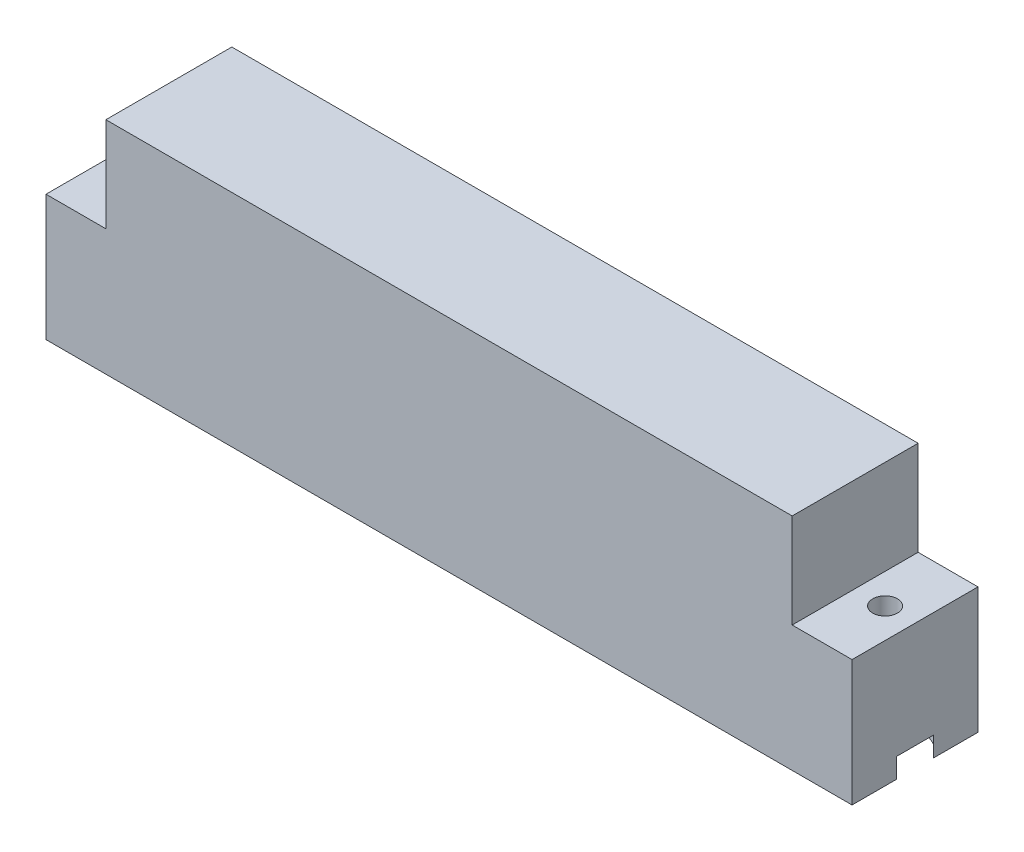
SolidWorks part; units mm, degrees
other "Markup1"
sketch "Sketch8" plane through (81.28, 0, 0) normal (0.1042, -0.9852, 0.1359) x (-0.4456, -0.1684, -0.8792)
ref_plane "Front Plane" through (0, 0, 0) normal (0, 0, 1) x (1, 0, 0)
ref_plane "Top Plane" through (0, 0, 0) normal (0, 1, 0) x (1, 0, 0)
ref_plane "Right Plane" through (0, 0, 0) normal (1, 0, 0) x (0, 0, -1)
sketch "Sketch1" plane through (0, 0, 0) normal (0, 1, 0) x (1, 0, 0)
  line L1 (0, 0) -> (81.28, 0)
  line L2 (0, 0) -> (0, 12.7)
  line L3 (0, 12.7) -> (81.28, 12.7)
  line L4 (81.28, 0) -> (81.28, 12.7)
  line L5 (0, 0) -> (81.28, 12.7) construction
  line L6 (0, 12.7) -> (81.28, 0) construction
  point P4 (40.64, 6.35)
  dimension "D1" = 12.7
  dimension "D2" = 81.28
extrude "Boss-Extrude1" add sketch "Sketch1" along normal blind 12.7
sketch "Sketch2" plane through (0, 12.7, 0) normal (0, 1, 0) x (1, 0, 0)
  line L0 (0, 0) -> (6.0376, 0) construction
  line L1 (0, 0) -> (81.28, 0) construction
  line L2 (81.28, 12.7) -> (0, 12.7) construction
  line L8 (6.0376, 0) -> (75.2424, 0)
  line L9 (6.0376, 0) -> (6.0376, 12.7)
  line L10 (6.0376, 12.7) -> (75.2424, 12.7)
  line L11 (75.2424, 0) -> (75.2424, 12.7)
  line L12 (6.0376, 0) -> (75.2424, 12.7) construction
  line L13 (6.0376, 12.7) -> (75.2424, 0) construction
  line L14 (81.28, 0) -> (81.28, 12.7) construction
  point P7 (14.605, 6.35)
  point P8 (40.64, 6.35)
  point P9 (41.275, 6.35)
  dimension "D1" = 69.2048
  dimension "D2" = 6.0376
  dimension "D3" = 6.0376
extrude "Boss-Extrude2" add sketch "Sketch2" along normal blind 9.525
sketch "Sketch3" plane through (0, 12.7, 0) normal (0, 1, 0) x (1, 0, 0)
  line L0 (3.0188, 12.7) -> (3.0188, 6.35) construction
  line L1 (6.0376, 12.7) -> (0, 12.7) construction
  line L2 (78.2612, 12.7) -> (78.2612, 6.35) construction
  line L3 (81.28, 12.7) -> (75.2424, 12.7) construction
  circle A0 centre (3.0188, 6.35) radius 1.25
  circle A2 centre (78.2612, 6.35) radius 1.25
  dimension "D1" = 2.5
  dimension "D2" = 2.5
extrude "Cut-Extrude2" cut sketch "Sketch3" against normal through all contours A0 | A2
sketch "Sketch5" plane through (0, 0, 0) normal (0, -1, 0) x (1, 0, 0)
  circle A0 centre (3.0188, -6.35) radius 3.556
  circle A1 centre (78.2612, -6.35) radius 3.556
  dimension "D1" = 7.112
  dimension "D2" = 7.112
extrude "Cut-Extrude3" cut sketch "Sketch5" against normal blind 1.999 contours A1 | A0
sketch "Sketch6" plane through (0, 0, -12.7) normal (0, 0, -1) x (-1, 0, 0)
  line L0 (-75.2424, 22.225) -> (-40.64, 22.225) construction
  line L1 (-75.2424, 22.225) -> (-6.0376, 22.225) construction
  line L2 (-40.64, 22.225) -> (-40.64, 13.2994) construction
  circle A0 centre (-40.64, 13.2994) radius 2.1996
  dimension "D1" = 8.9256
extrude "Cut-Extrude4" cut sketch "Sketch6" against normal blind 1.27
sketch "Sketch7" plane through (0, 0, -11.43) normal (0, 0, -1) x (-1, 0, 0)
  circle A0 centre (-40.64, 13.2994) radius 1.65
extrude "Cut-Extrude5" cut sketch "Sketch7" against normal blind 6.604
